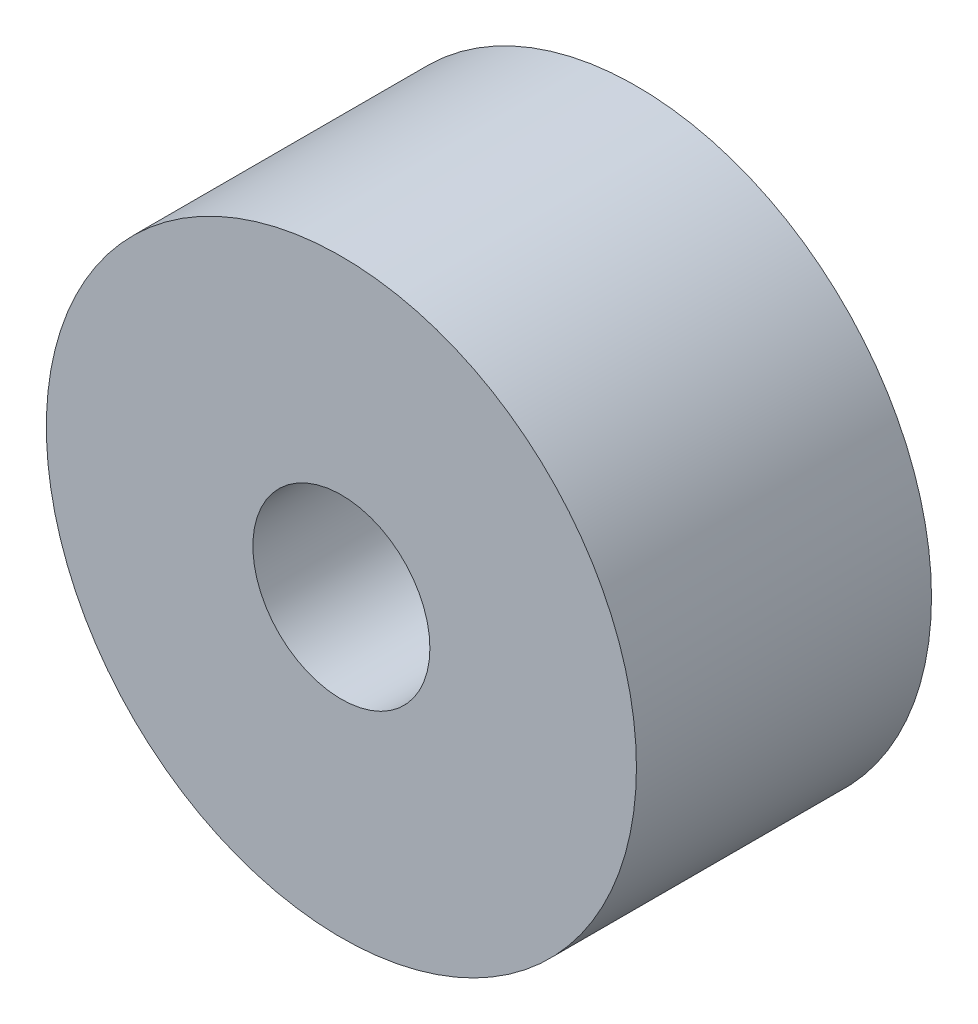
SolidWorks part; units mm, degrees
ref_plane "Plan de face" through (0, 0, 0) normal (0, 0, 1) x (1, 0, 0)
ref_plane "Plan de dessus" through (0, 0, 0) normal (0, 1, 0) x (1, 0, 0)
ref_plane "Plan de droite" through (0, 0, 0) normal (1, 0, 0) x (0, 0, -1)
sketch "Esquisse1" plane through (0, 0, 0) normal (0, 0, 1) x (1, 0, 0)
  circle A0 centre (0, 0) radius 10
  circle A1 centre (0, 0) radius 3
  dimension "D1" = 20
  dimension "D2" = 6
extrude "Boss.-Extru.1" add sketch "Esquisse1" along normal blind 10
